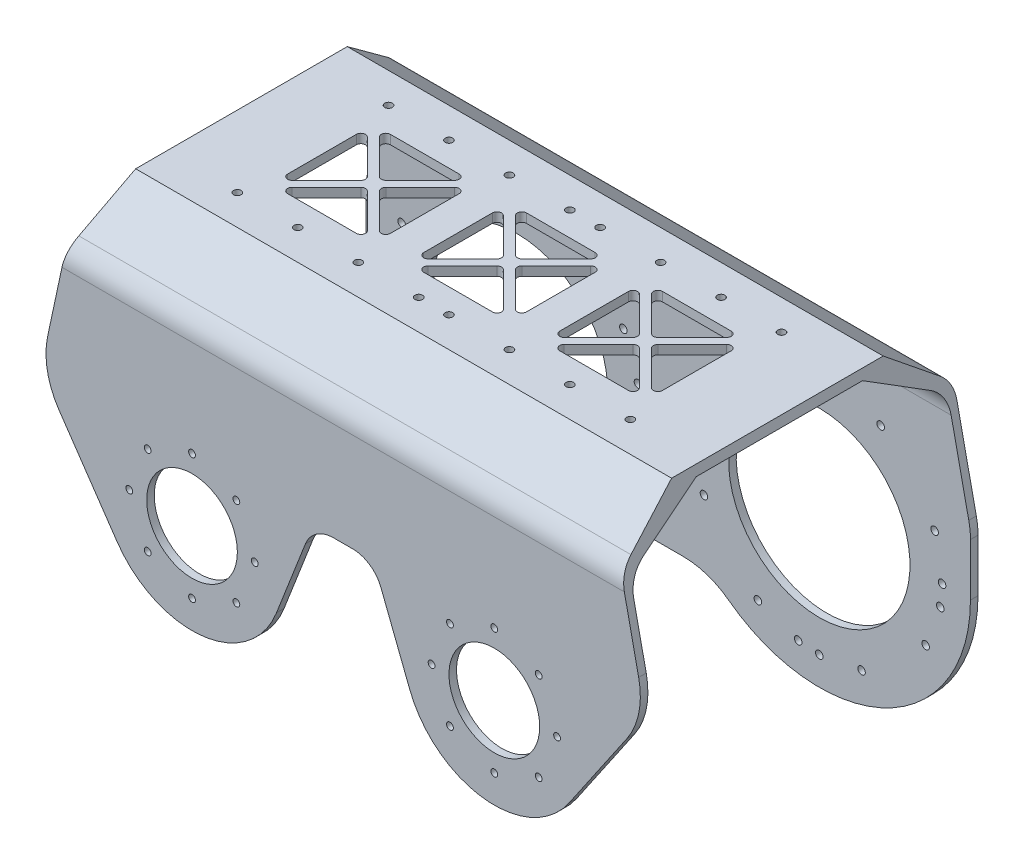
SolidWorks part; units mm, degrees
material "6061 合金"
ref_plane "前视基准面" through (0, 0, 0) normal (0, 0, 1) x (1, 0, 0)
ref_plane "上视基准面" through (0, 0, 0) normal (0, 1, 0) x (1, 0, 0)
ref_plane "右视基准面" through (0, 0, 0) normal (1, 0, 0) x (0, 0, -1)
other "Configuration Table"
sketch "草图1" plane through (0, 0, 0) normal (0, 0, 1) x (1, 0, 0)
  line L0 (0, 350.9244) -> (0, -92.7876) construction
  line L1 (-181.3077, 0) -> (720.1521, 0) construction
  line L5 (200, 120) -> (200, 0)
  line L6 (-200, 120) -> (-200, 0)
  line L8 (-200, 120) -> (-200, 180)
  line L9 (-200, 180) -> (200, 180)
  line L10 (200, 180) -> (200, 120)
  line L11 (-28.5857, -70) -> (28.5857, -70)
  circle A0 centre (100, 0) radius 60
  circle A1 centre (100, 0) radius 85 construction
  arc A2 (28.5857, -70) -> (200, 0) centre (100, 0) ccw
  circle A3 centre (-100, 0) radius 85 construction
  circle A4 centre (-100, 0) radius 60
  arc A5 (-28.5857, -70) -> (-200, 0) centre (-100, 0) cw
  point P16 (0, 176.5389)
  point P17 (0, 80)
  dimension "D1" = 120
  dimension "D2" = 170
  dimension "D4" = 200
  dimension "D3" = 100
  dimension "D5" = 70
  dimension "D9" = 400
  dimension "D10" = 180
extrude "凸台-拉伸1" add sketch "草图1" along normal blind 220
sketch "草图2" plane through (0, 0, 0) normal (1, 0, 0) x (0, 0, -1)
  line L0 (-110, 291.5151) -> (-110, -211.064) construction
  line L1 (0, 0) -> (0, 180) construction
  line L2 (-220, 0) -> (-220, 180) construction
  line L5 (-215, 111.1325) -> (-215, -188.8675)
  line L6 (-215, -188.8675) -> (-5, -188.8675)
  line L7 (-5, 111.1325) -> (-5, -188.8675)
  line L8 (0, -100) -> (0, 0) construction
  line L10 (-215, 111.1325) -> (-165, 140)
  line L11 (-165, 140) -> (-55, 140)
  line L12 (-5, 111.1325) -> (-55, 140)
  line L13 (-220, 180) -> (0, 180) construction
  point P15 (-110, 140)
  dimension "D1" = 5
  dimension "D2" = 40
  dimension "D3" = 300
  dimension "D4" = 30
  dimension "D5" = 110
extrude "切除-拉伸1" cut sketch "草图2" against normal through all both and the other way through all
sketch "草图3" plane through (0, 0, 0) normal (1, 0, 0) x (0, 0, -1)
  line L0 (-110, 274.1056) -> (-110, -160.0053) construction
  line L1 (0, 0) -> (0, 180) construction
  line L2 (-220, 0) -> (-220, 180) construction
  line L3 (-180, 180) -> (-180, 146)
  line L4 (-220, 180) -> (0, 180) construction
  line L5 (-55, 140) -> (-165, 140) construction
  line L6 (-180, 146) -> (-220, 115)
  line L7 (-220, 0) -> (-220, 180) construction
  line L8 (-220, 115) -> (-220, 180)
  line L9 (-220, 180) -> (-180, 180)
  line L10 (0, 180) -> (-40, 180)
  line L11 (0, 115) -> (0, 180)
  line L12 (-40, 146) -> (0, 115)
  line L13 (-40, 180) -> (-40, 146)
  dimension "D1" = 65
  dimension "D2" = 140
  dimension "D3" = 6
extrude "切除-拉伸2" cut sketch "草图3" against normal through all both and the other way through all
sketch "草图4" plane through (0, 0, 0) normal (0, 0, -1) x (-1, 0, 0)
  line L0 (0, 284.6971) -> (0, -204.9481) construction
  line L1 (-100, 0) -> (-72.051, 76.2917) construction
  line L2 (-100, 0) -> (-100, 81.25) construction
  line L3 (-100, 0) -> (-113.9413, 80.045) construction
  line L4 (-100, 0) -> (-140.625, 70.3646) construction
  line L5 (100, 0) -> (140.625, 70.3646) construction
  line L6 (100, 0) -> (113.9413, 80.045) construction
  line L7 (100, 0) -> (100, 81.25) construction
  line L8 (100, 0) -> (72.051, 76.2917) construction
  circle A0 centre (-100, 0) radius 81.25 construction
  circle A1 centre (-72.051, 76.2917) radius 2.5
  circle A2 centre (-100, 81.25) radius 2.5
  circle A3 centre (-113.9413, 80.045) radius 2.5
  circle A4 centre (-140.625, 70.3646) radius 2.5
  circle A5 centre (-23.7083, -27.949) radius 2.5
  circle A6 centre (-18.75, 0) radius 2.5
  circle A7 centre (-19.955, 13.9413) radius 2.5
  circle A8 centre (-29.6354, 40.625) radius 2.5
  circle A9 centre (-127.949, -76.2917) radius 2.5
  circle A10 centre (-100, -81.25) radius 2.5
  circle A11 centre (-86.0587, -80.045) radius 2.5
  circle A12 centre (-59.375, -70.3646) radius 2.5
  circle A13 centre (-176.2917, 27.949) radius 2.5
  circle A14 centre (-181.25, 0) radius 2.5
  circle A15 centre (-180.045, -13.9413) radius 2.5
  circle A16 centre (-170.3646, -40.625) radius 2.5
  circle A17 centre (100, 0) radius 81.25 construction
  circle A18 centre (170.3646, -40.625) radius 2.5
  circle A19 centre (180.045, -13.9413) radius 2.5
  circle A20 centre (181.25, 0) radius 2.5
  circle A21 centre (176.2917, 27.949) radius 2.5
  circle A22 centre (59.375, -70.3646) radius 2.5
  circle A23 centre (86.0587, -80.045) radius 2.5
  circle A24 centre (100, -81.25) radius 2.5
  circle A25 centre (127.949, -76.2917) radius 2.5
  circle A26 centre (29.6354, 40.625) radius 2.5
  circle A27 centre (19.955, 13.9413) radius 2.5
  circle A28 centre (18.75, 0) radius 2.5
  circle A29 centre (23.7083, -27.949) radius 2.5
  circle A30 centre (140.625, 70.3646) radius 2.5
  circle A31 centre (113.9413, 80.045) radius 2.5
  circle A32 centre (100, 81.25) radius 2.5
  circle A33 centre (72.051, 76.2917) radius 2.5
  point P41 (-100, 0)
  point P74 (100, 0)
  dimension "D1" = 162.5
  dimension "D5" = 5
  dimension "D2" = 30
  dimension "D3" = 30
  dimension "D4" = 9.88
  dimension "D6" = 4
extrude "切除-拉伸3" cut sketch "草图4" against normal blind 32.5
sketch "草图5" plane through (0, 0, 220) normal (0, 0, 1) x (1, 0, 0)
  circle A0 centre (-100, 0) radius 60 construction
  circle A1 centre (100, 0) radius 60 construction
  circle A2 centre (-100, 0) radius 60
  circle A3 centre (100, 0) radius 60
  circle A4 centre (100, 0) radius 30
  circle A5 centre (-100, 0) radius 30
  dimension "D1" = 60
extrude "凸台-拉伸2" add sketch "草图5" against normal up to surface (5 mm away) up to face at (160, 0, 215)
sketch "草图6" plane through (0, 0, 220) normal (0, 0, 1) x (1, 0, 0)
  line L0 (0, 0) -> (0, 283.4074) construction
  line L1 (100, 0) -> (100, 76.6247) construction
  line L2 (-100, 0) -> (-100, 76.6247) construction
  circle A0 centre (100, 0) radius 41.5 construction
  circle A1 centre (100, 41.5) radius 2.25
  circle A2 centre (129.3449, 29.3449) radius 2.25
  circle A3 centre (141.5, 0) radius 2.25
  circle A4 centre (129.3449, -29.3449) radius 2.25
  circle A5 centre (100, -41.5) radius 2.25
  circle A6 centre (70.6551, -29.3449) radius 2.25
  circle A7 centre (58.5, 0) radius 2.25
  circle A8 centre (70.6551, 29.3449) radius 2.25
  circle A9 centre (-100, 0) radius 41.5 construction
  circle A10 centre (-70.6551, 29.3449) radius 2.25
  circle A11 centre (-58.5, 0) radius 2.25
  circle A12 centre (-70.6551, -29.3449) radius 2.25
  circle A13 centre (-100, -41.5) radius 2.25
  circle A14 centre (-129.3449, -29.3449) radius 2.25
  circle A15 centre (-141.5, 0) radius 2.25
  circle A16 centre (-129.3449, 29.3449) radius 2.25
  circle A17 centre (-100, 41.5) radius 2.25
  point P26 (100, 0)
  point P44 (-100, 0)
  dimension "D1" = 83
  dimension "D2" = 4.5
  dimension "D3" = 8
extrude "切除-拉伸4" cut sketch "草图6" against normal up to surface (5 mm away) up to face at (0, -5.4819, 215)
sketch "草图7" plane through (0, 0, 220) normal (0, 0, 1) x (1, 0, 0)
  line L0 (0, 0) -> (0, 252.6042) construction
  line L1 (0, 0) -> (0, -112.8952) construction
  line L2 (-20, 40) -> (20, 40)
  line L3 (20, 40) -> (44.1003, -21.7995)
  line L4 (170, 180) -> (200, 180)
  line L5 (-200, 180) -> (200, 180) construction
  line L6 (200, 180) -> (200, 40)
  line L7 (200, 0) -> (200, 115) construction
  line L8 (200, 40) -> (170, 180)
  line L9 (-200, 180) -> (-200, 40)
  line L10 (-170, 180) -> (-200, 180)
  line L11 (-200, 40) -> (-170, 180)
  line L12 (200, 40) -> (149.5399, -33.8497)
  line L13 (-28.5857, -70) -> (28.5857, -70) construction
  line L14 (200, 0) -> (200, 40)
  line L15 (-28.5857, -70) -> (28.5857, -70)
  line L16 (-200, 0) -> (-200, 40)
  line L17 (-200, 40) -> (-149.5399, -33.8497)
  line L18 (-20, 40) -> (-44.1003, -21.7995)
  arc A0 (44.1003, -21.7995) -> (149.5399, -33.8497) centre (100, 0) ccw
  arc A1 (28.5857, -70) -> (200, 0) centre (100, 0) ccw construction
  arc A2 (28.5857, -70) -> (200, 0) centre (100, 0) ccw
  arc A3 (-28.5857, -70) -> (-200, 0) centre (-100, 0) cw
  arc A4 (-44.1003, -21.7995) -> (-149.5399, -33.8497) centre (-100, 0) cw
  point P22 (0, -70)
  point P32 (0, 40)
  line M32 (200, 115) -> (-200, 115)
  line M33 (-200, 115) -> (-200, 0)
  arc M34 (-200, 0) -> (-28.5857, -70) centre (-100, 0) ccw
  line M35 (-28.5857, -70) -> (28.5857, -70)
  arc M36 (28.5857, -70) -> (200, 0) centre (100, 0) ccw
  line M37 (200, 0) -> (200, 115)
  dimension "D1" = 120
  dimension "D2" = 30
  dimension "D3" = 140
  dimension "D4" = 40
  dimension "D5" = 20
extrude "切除-拉伸5" cut sketch "草图7" against normal blind 10 contours L8 L6 L4 M32 | L8 M37 M32 | L18 A4 L17 L12 A0 L3 L2 M33 M34 M35 M36 M37 | L11 L10 L9 M32 | L11 M33 M32
sketch "草图8" plane through (0, 0, 0) normal (0, 0, -1) x (-1, 0, 0)
  line L0 (200, 40) -> (170, 180) construction
  line L1 (200, 180) -> (200, 40) construction
  line L2 (170, 180) -> (200, 180) construction
  line L3 (-200, 40) -> (-170, 180) construction
  line L4 (-200, 180) -> (-200, 40) construction
  line L5 (-170, 180) -> (-200, 180) construction
  line L6 (200, 40) -> (170, 180)
  line L7 (200, 180) -> (200, 40)
  line L8 (170, 180) -> (200, 180)
  line L9 (-200, 40) -> (-170, 180)
  line L10 (-200, 180) -> (-200, 40)
  line L11 (-170, 180) -> (-200, 180)
extrude "切除-拉伸6" cut sketch "草图8" against normal blind 381
fillet "圆角1" radius 50 6 edges at (-200, 40, 217.5) (200, 40, 217.5) (200, 40, 2.5) (28.5857, -70, 2.5) (-28.5857, -70, 2.5) (-200, 40, 2.5)
fillet "圆角2" radius 20 6 edges at (0, 111.1325, 5) (0, 111.1325, 215) (-20, 40, 217.5) (20, 40, 217.5) (0, 115, 0) (0, 115, 220)
sketch "草图9" plane through (0, 0, 220) normal (0, 0, 1) x (1, 0, 0)
  line L1 (-235.8074, 239.4268) -> (177.2857, 239.4268)
  line L2 (-235.8074, 239.4268) -> (-235.8074, 146)
  line L3 (-235.8074, 146) -> (177.2857, 146)
  line L4 (177.2857, 239.4268) -> (177.2857, 146)
extrude "切除-拉伸7" cut sketch "草图9" against normal blind 381
sketch "草图10" plane through (0, 146, 0) normal (0, 1, 0) x (1, 0, 0)
  line L0 (-219.3102, -110) -> (241.5322, -110) construction
  line L1 (0, 0) -> (0, -250.3427) construction
  line L2 (-186.0292, 0) -> (186.0292, 0) construction
  line L3 (-177.2857, -180) -> (177.2857, -180) construction
  line L4 (-177.2857, -40) -> (177.2857, -40) construction
  line L5 (60, -76) -> (120, -76)
  line L6 (120, -76) -> (90, -106)
  line L7 (90, -106) -> (60, -76)
  line L8 (90, 38.8036) -> (90, -139.59) construction
  line L9 (94, -110) -> (124, -80)
  line L10 (124, -80) -> (124, -140)
  line L11 (124, -140) -> (94, -110)
  line L12 (90, -114) -> (120, -144)
  line L13 (120, -144) -> (60, -144)
  line L14 (60, -144) -> (90, -114)
  line L15 (86, -110) -> (56, -140)
  line L16 (56, -140) -> (56, -80)
  line L17 (56, -80) -> (86, -110)
  line L18 (4, -110) -> (34, -80)
  line L19 (34, -80) -> (34, -140)
  line L20 (34, -140) -> (4, -110)
  line L21 (0, -106) -> (-30, -76)
  line L22 (-30, -76) -> (30, -76)
  line L23 (30, -76) -> (0, -106)
  line L24 (-4, -110) -> (-34, -140)
  line L25 (-34, -140) -> (-34, -80)
  line L26 (-34, -80) -> (-4, -110)
  line L27 (0, -114) -> (30, -144)
  line L28 (30, -144) -> (-30, -144)
  line L29 (-30, -144) -> (0, -114)
  line L30 (-86, -110) -> (-56, -80)
  line L31 (-56, -80) -> (-56, -140)
  line L32 (-56, -140) -> (-86, -110)
  line L33 (-90, -106) -> (-120, -76)
  line L34 (-120, -76) -> (-60, -76)
  line L35 (-60, -76) -> (-90, -106)
  line L36 (-94, -110) -> (-124, -140)
  line L37 (-124, -140) -> (-124, -80)
  line L38 (-124, -80) -> (-94, -110)
  line L39 (-90, -114) -> (-60, -144)
  line L40 (-60, -144) -> (-120, -144)
  line L41 (-120, -144) -> (-90, -114)
  circle A0 centre (130, -60) radius 2.5
  circle A1 centre (50, -60) radius 2.5
  circle A4 centre (-50, -60) radius 2.5
  circle A5 centre (-130, -60) radius 2.5
  circle A6 centre (130, -160) radius 2.5
  circle A7 centre (50, -160) radius 2.5
  circle A8 centre (-50, -160) radius 2.5
  circle A9 centre (-130, -160) radius 2.5
  circle A10 centre (10, -60) radius 2.5
  circle A11 centre (90, -60) radius 2.5
  circle A12 centre (90, -160) radius 2.5
  circle A13 centre (10, -160) radius 2.5
  circle A14 centre (-90, -160) radius 2.5
  circle A15 centre (-10, -160) radius 2.5
  circle A16 centre (-90, -60) radius 2.5
  circle A17 centre (-10, -60) radius 2.5
  point P34 (90, -110)
  point P44 (90, -110)
  dimension "D1" = 5
  dimension "D12" = 40
  dimension "D14" = 80
  dimension "D2" = 80
  dimension "D3" = 50
  dimension "D4" = 50
  dimension "D5" = 45
  dimension "D6" = 45
  dimension "D7" = 60
  dimension "D8" = 4
  dimension "D9" = 4
  dimension "D11" = 22
  dimension "D10" = 3
  dimension "D13" = 2
extrude "切除-拉伸8" cut sketch "草图10" against normal blind 10
fillet "圆角3" radius 3 36 edges at (-120, 143, 76) (-90, 143, 106) (-60, 143, 76) (-56, 143, 80) (-56, 143, 140) (-86, 143, 110) (-94, 143, 110) (-124, 143, 80) (-124, 143, 140) (-120, 143, 144) (-90, 143, 114) (-60, 143, 144) (30, 143, 76) (0, 143, 106) (-30, 143, 76) (-4, 143, 110) (-34, 143, 80) (-34, 143, 140) (-30, 143, 144) (30, 143, 144) (0, 143, 114) (4, 143, 110) (34, 143, 140) (34, 143, 80) (56, 143, 80) (86, 143, 110) (56, 143, 140) (60, 143, 144) (90, 143, 114) (120, 143, 144) (124, 143, 140) (94, 143, 110) (90, 143, 106) (60, 143, 76) (120, 143, 76) (124, 143, 80)
